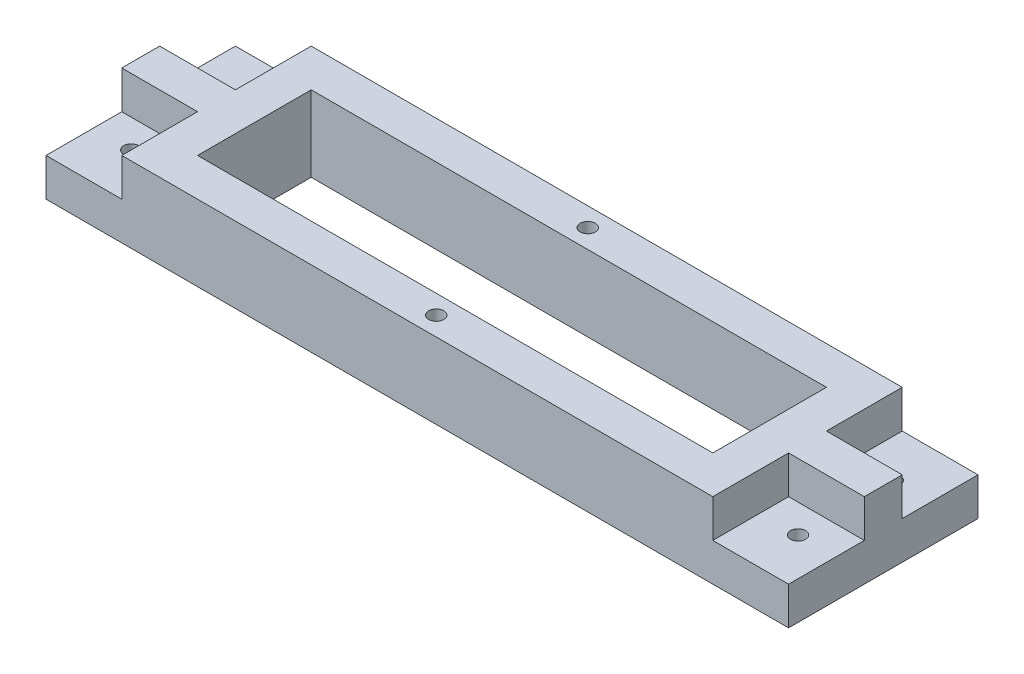
SolidWorks part; units mm, degrees
ref_plane "Front Plane" through (0, 0, 0) normal (0, 0, 1) x (1, 0, 0)
ref_plane "Top Plane" through (0, 0, 0) normal (0, 1, 0) x (1, 0, 0)
ref_plane "Right Plane" through (0, 0, 0) normal (1, 0, 0) x (0, 0, -1)
sketch "Sketch1" plane through (0, 0, 0) normal (0, 1, 0) x (1, 0, 0)
  line L1 (-39, 12.5) -> (39, 12.5)
  line L2 (-39, 12.5) -> (-39, -12.5)
  line L3 (-39, -12.5) -> (39, -12.5)
  line L4 (39, 12.5) -> (39, -12.5)
  line L5 (-39, 12.5) -> (39, -12.5) construction
  line L6 (-39, -12.5) -> (39, 12.5) construction
  point P0 (0, 0)
  dimension "D1" = 78
  dimension "D2" = 25
extrude "Boss-Extrude1" add sketch "Sketch1" along normal blind 10
sketch "Sketch2" plane through (0, 10, 0) normal (0, 1, 0) x (1, 0, 0)
  line L0 (0, 12.5) -> (0, 7.5)
  line L1 (39, 12.5) -> (-39, 12.5) construction
  line L2 (-39, 0) -> (-34, 0)
  line L3 (-39, 12.5) -> (-39, -12.5) construction
  line L9 (34, -7.5) -> (-34, -7.5)
  line L10 (34, -7.5) -> (34, 7.5)
  line L11 (34, 7.5) -> (-34, 7.5)
  line L12 (-34, -7.5) -> (-34, 7.5)
  line L13 (34, -7.5) -> (-34, 7.5) construction
  line L14 (34, 7.5) -> (-34, -7.5) construction
  point P9 (0, 0)
  point P10 (0, 0)
extrude "Cut-Extrude2" cut sketch "Sketch2" against normal blind 10 contours L12 L9 L10 L11
sketch "Sketch3" plane through (-39, 0, 0) normal (-1, 0, 0) x (0, 0, 1)
  line L0 (-12.5, 0) -> (-12.5, 5)
  line L1 (-12.5, 10) -> (-12.5, 0) construction
  line L2 (-12.5, 5) -> (12.5, 5)
  line L3 (12.5, 10) -> (12.5, 0) construction
  line L4 (12.5, 5) -> (12.5, 0)
  line L5 (12.5, 0) -> (-12.5, 0)
extrude "Boss-Extrude2" add sketch "Sketch3" along normal blind 10
sketch "Sketch4" plane through (39, 0, 0) normal (1, 0, 0) x (0, 0, -1)
  line L1 (-12.5, 5) -> (12.5, 5)
  line L2 (-12.5, 5) -> (-12.5, 0)
  line L3 (-12.5, 0) -> (12.5, 0)
  line L4 (12.5, 5) -> (12.5, 0)
extrude "Boss-Extrude3" add sketch "Sketch4" along normal blind 10
ref_plane "Plane1" through (0, 5, 0) normal (0, 1, 0) x (1, 0, 0)
sketch "Sketch6" plane through (0, 5, 0) normal (0, 1, 0) x (1, 0, 0)
  line L2 (39, 12.5) -> (39, -12.5) construction
  line L3 (-49, -2.5) -> (-39, -2.5)
  line L6 (49, 2.5) -> (49, -2.5)
  line L7 (49, -2.5) -> (39, -2.5)
  line L8 (39, -2.5) -> (39, 2.5)
  line L9 (49, 2.5) -> (39, 2.5)
  line L10 (0, -7.5) -> (0, -2.5)
  line L11 (34, -7.5) -> (-34, -7.5) construction
  line L12 (-49, 2.5) -> (-49, -2.5)
  line L13 (-49, 2.5) -> (-39, 2.5)
  line L14 (-39, -2.5) -> (-39, 2.5)
extrude "Boss-Extrude4" add sketch "Sketch6" along normal blind 5 contours L6 L9 L8 L7 | L3 L14 L13 L12
sketch "Sketch9" plane through (0, 0, 0) normal (0, -1, 0) x (1, 0, 0)
  line L0 (49, -12.5) -> (-49, -12.5) construction
  line L1 (-49, 12.5) -> (-39, 12.5) construction
  line L2 (-49, 12.5) -> (-49, -12.5) construction
  line L3 (-49, -12.5) -> (-39, -12.5) construction
  line L4 (-39, 12.5) -> (-39, -12.5) construction
  line L5 (-44, 12.5) -> (-44, 0) construction
  line L6 (-44, 0) -> (-41.3729, 0)
  line L7 (0, 7.5) -> (0, 4.835)
  line L8 (34, 7.5) -> (-34, 7.5) construction
  circle A0 centre (-44, 6.25) radius 1.75
  circle A1 centre (-44, -6.25) radius 1.75
  circle A2 centre (44, -6.25) radius 1.75
  circle A3 centre (44, 6.25) radius 1.75
  dimension "D1" = 3.5
extrude "Cut-Extrude5" cut sketch "Sketch9" against normal blind 2 contours A0 | A1 | A3 | A2
sketch "Sketch10" plane through (0, 2, 0) normal (0, -1, 0) x (1, 0, 0)
  line L0 (-49, 0) -> (-47.2279, 0)
  line L1 (-49, -12.5) -> (-49, 12.5) construction
  line L2 (0, -7.5) -> (0, -5.5971)
  line L3 (34, -7.5) -> (-34, -7.5) construction
  circle A0 centre (-44, 6.25) radius 1
  circle A1 centre (-44, -6.25) radius 1
  circle A2 centre (44, -6.25) radius 1
  circle A3 centre (44, 6.25) radius 1
extrude "Cut-Extrude6" cut sketch "Sketch10" against normal blind 13 contours A0 | A1 | A3 | A2
sketch "Sketch11" plane through (0, 0, 0) normal (0, -1, 0) x (1, 0, 0)
  line L0 (0, 7.5) -> (0, 12.5)
  line L1 (34, 7.5) -> (-34, 7.5) construction
  line L2 (-49, 12.5) -> (49, 12.5) construction
  circle A0 centre (0, 10) radius 1.75
  dimension "D1" = 3.5
extrude "Cut-Extrude7" cut sketch "Sketch11" against normal blind 1.5 contours L0 A0 | L0 A0
sketch "Sketch12" plane through (0, 1.5, 0) normal (0, -1, 0) x (1, 0, 0)
  circle A0 centre (0, 10) radius 1
  dimension "D1" = 2
extrude "Cut-Extrude8" cut sketch "Sketch12" against normal blind 10.5
sketch "Sketch13" plane through (0, 0, 0) normal (0, -1, 0) x (1, 0, 0)
  line L0 (0, -12.5) -> (0, -11)
  line L1 (49, -12.5) -> (-49, -12.5) construction
  line L2 (34, -7.5) -> (-34, -7.5) construction
  line L3 (0, -9) -> (0, -7.5)
  circle A0 centre (0, -10) radius 1
  dimension "D1" = 2
extrude "Cut-Extrude9" cut sketch "Sketch13" against normal blind 15 contours A0
sketch "Sketch14" plane through (0, 0, 0) normal (0, -1, 0) x (1, 0, 0)
  circle A0 centre (0, -10) radius 1.75
  dimension "D1" = 3.5
extrude "Cut-Extrude11" cut sketch "Sketch14" against normal blind 1.5
